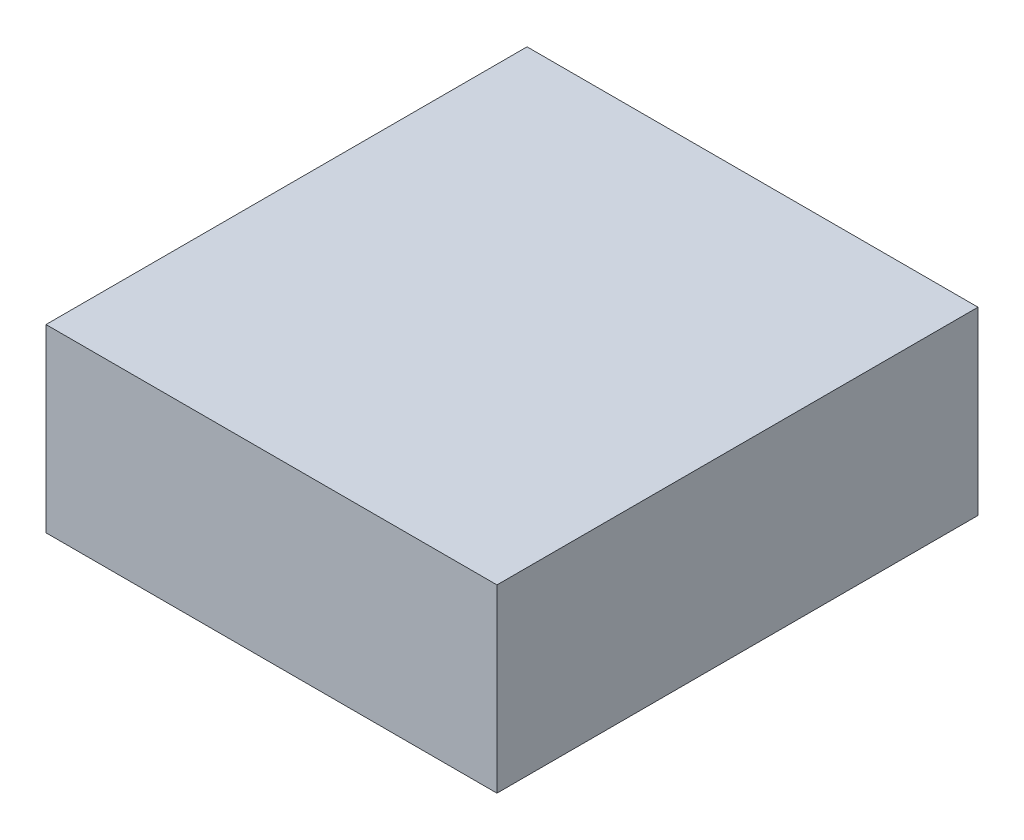
SolidWorks part; units mm, degrees
ref_plane "Ebene vorne" through (0, 0, 0) normal (0, 0, 1) x (1, 0, 0)
ref_plane "Ebene oben" through (0, 0, 0) normal (0, 1, 0) x (1, 0, 0)
ref_plane "Ebene rechts" through (0, 0, 0) normal (1, 0, 0) x (0, 0, -1)
sketch "Skizze2" plane through (0, 0, 0) normal (0, 1, 0) x (1, 0, 0)
  line L0 (-15, 0) -> (15, 0) construction
  line L1 (-15, 16) -> (15, 16)
  line L2 (-15, 16) -> (-15, -16)
  line L3 (-15, -16) -> (15, -16)
  line L4 (15, 16) -> (15, -16)
  line L5 (-15, 16) -> (15, -16) construction
  line L6 (-15, -16) -> (15, 16) construction
  line L7 (0, 16) -> (0, -16) construction
  point P0 (0, 0)
  dimension "D1" = 30
  dimension "D2" = 32
extrude "Aufsatz-Linear austragen1" add sketch "Skizze2" along normal blind 12
